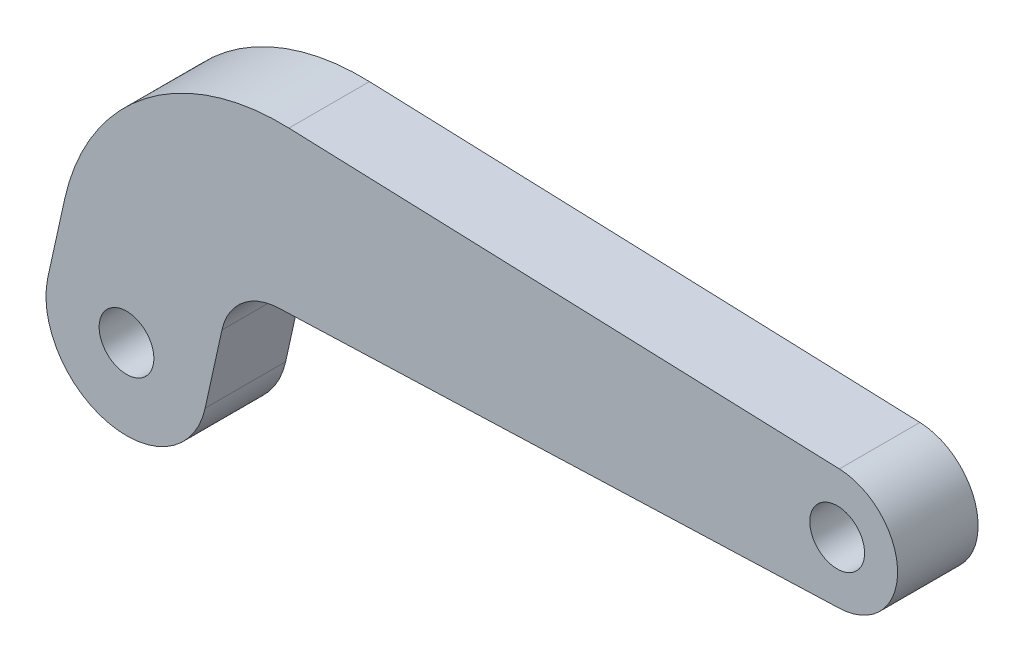
SolidWorks part; units mm, degrees
ref_plane "Front Plane" through (0, 0, 0) normal (0, 0, 1) x (1, 0, 0)
ref_plane "Top Plane" through (0, 0, 0) normal (0, 1, 0) x (1, 0, 0)
ref_plane "Right Plane" through (0, 0, 0) normal (1, 0, 0) x (0, 0, -1)
sketch "Sketch1" plane through (0, 0, 0) normal (0, 0, 1) x (1, 0, 0)
  line L0 (56.2124, 19.49) -> (12.8079, 21.0619)
  line L2 (56.2124, 9.9712) -> (12.0035, 8.3702)
  line L5 (0, 0) -> (56.04, 14.7306) construction
  line L6 (6.201, -1.3676) -> (7.5251, 4.6365)
  line L7 (-6.201, 1.3676) -> (-4.8769, 7.3716)
  line L8 (56.04, 14.7306) -> (12.8079, 14.7306) construction
  line L9 (12.8079, 21.0619) -> (12.8079, 8.3994) construction
  circle A0 centre (0, 0) radius 2.159
  circle A1 centre (56.04, 14.7306) radius 2.159
  arc A2 (56.2124, 9.9712) -> (56.2124, 19.49) centre (56.04, 14.7306) ccw
  arc A4 (-6.201, 1.3676) -> (6.201, -1.3676) centre (0, 0) ccw
  arc A5 (12.0035, 8.3702) -> (7.5251, 4.6365) centre (12.1759, 3.6108) ccw
  arc A6 (12.8079, 21.0619) -> (-4.8769, 7.3716) centre (12.1759, 3.6108) ccw
  arc A7 (12.2827, 3.2286) -> (12.1759, 3.6108) centre (0, 0) ccw construction
  point P9 (12.2827, 3.2286)
  point P19 (0, 0)
  point P20 (25.175, 14.6663)
  point P22 (12.8079, 14.7306)
  point P23 (27.8975, 14.9298)
other "Pen Sketch1" parameters "D1"=16.3026, "D4"=5.6114, "D5"=4.767, "D6"=3.6226, "D7"=4.2424, "D8"=17.8584, "D2"=28.8294, "D3"=8.5598
extrude "Boss-Extrude1" add sketch "Sketch1" along normal mid plane 6.35
